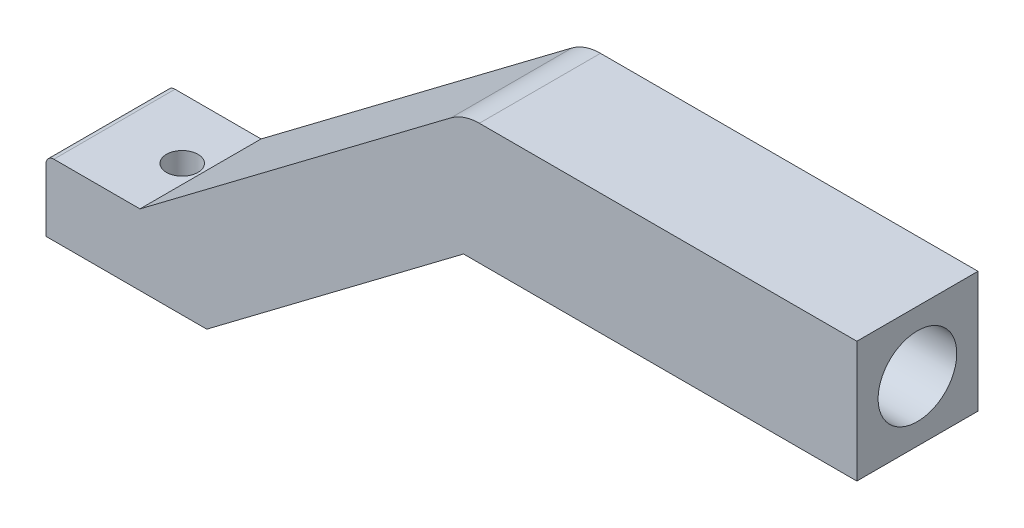
SolidWorks part; units mm, degrees
material "6061 合金"
ref_plane "前视基准面" through (0, 0, 0) normal (0, 0, 1) x (1, 0, 0)
ref_plane "上视基准面" through (0, 0, 0) normal (0, 1, 0) x (1, 0, 0)
ref_plane "右视基准面" through (0, 0, 0) normal (1, 0, 0) x (0, 0, -1)
other "Configuration Table"
sketch "草图1" plane through (0, 0, 0) normal (0, 0, 1) x (1, 0, 0)
  line L0 (0, 0) -> (16.3227, 12.3)
  line L1 (16.3227, 12.3) -> (41.3227, 12.3)
  line L2 (41.3227, 20) -> (41.3227, 12.3)
  line L3 (41.3227, 20) -> (16.3227, 20)
  line L4 (16.3227, 20) -> (-4.2465, 4.5)
  line L5 (-10.2182, 0) -> (0, 0)
  line L6 (16.3227, 20) -> (16.3227, 12.3) construction
  line L7 (-4.2465, 4.5) -> (-10.2182, 4.5)
  line L8 (-10.2182, 4.5) -> (-10.2182, 0)
  line L9 (-4.2465, 4.5) -> (-10.2182, 0) construction
  dimension "D1" = 20
  dimension "D2" = 25
  dimension "D3" = 7.7
  dimension "D4" = 143
  dimension "D5" = 4.5
extrude "主要外形" add sketch "草图1" along normal blind 7.7
fillet "圆角1" radius 3 1 edges at (16.3227, 20, 3.85)
sketch "草图4" plane through (41.3227, 0, 0) normal (1, 0, 0) x (0, 0, -1)
  line L0 (-7.7, 16.15) -> (0, 16.15) construction
  line L1 (-7.7, 12.3) -> (-7.7, 20) construction
  line L2 (0, 12.3) -> (0, 20) construction
  line L3 (-3.85, 20) -> (-3.85, 12.3) construction
  line L4 (-7.7, 20) -> (0, 20) construction
  line L5 (-7.7, 12.3) -> (0, 12.3) construction
  circle A0 centre (-3.85, 16.15) radius 2.5
  dimension "D1" = 5
extrude "和铁芯的连接孔" cut sketch "草图4" against normal blind 10
cosmetic thread "装饰螺纹线1" parameters "D2"=6
sketch "草图5" plane through (0, 0, 0) normal (0, -1, 0) x (1, 0, 0)
  line L0 (-10.2182, 3.85) -> (0, 3.85) construction
  line L1 (-10.2182, 7.7) -> (-10.2182, 0) construction
  line L2 (0, 7.7) -> (0, 0) construction
  line L3 (-5.1091, 7.7) -> (-5.1091, 0) construction
  line L4 (-10.2182, 7.7) -> (0, 7.7) construction
  line L5 (-10.2182, 0) -> (0, 0) construction
  line L9 (-8.2, 3.85) -> (-5.4091, 3.85) construction
  circle A1 centre (-5.4091, 3.85) radius 1
  point P0 (0, 0)
  point P1 (-5.1091, 3.85)
  point P20 (-5.4091, 3.85)
  dimension "D1" = 2
  dimension "D2" = 0.3
extrude "和平射铲的连接孔" cut sketch "草图5" against normal through all
cosmetic thread "装饰螺纹线3" parameters "D1"=6, "D2"=3
fillet "圆角3" radius 0.5 1 edges at (-10.2182, 4.5, 3.85)
